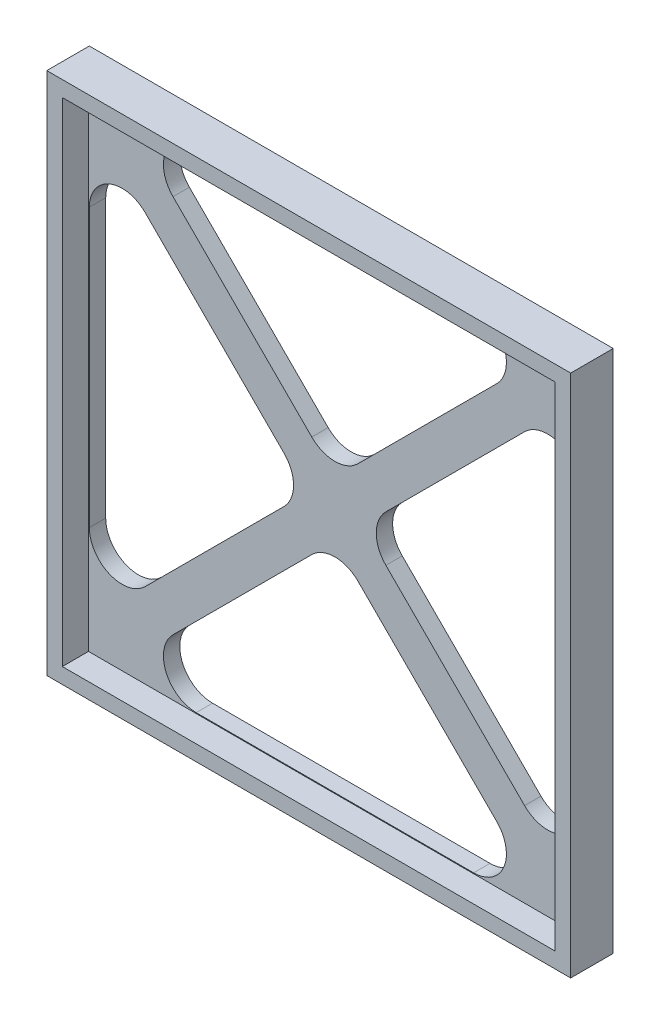
SolidWorks part; units mm, degrees
ref_plane "Front Plane" through (0, 0, 0) normal (0, 0, 1) x (1, 0, 0)
ref_plane "Top Plane" through (0, 0, 0) normal (0, 1, 0) x (1, 0, 0)
ref_plane "Right Plane" through (0, 0, 0) normal (1, 0, 0) x (0, 0, -1)
sketch "Sketch2" plane through (0, 0, 0) normal (0, 0, 1) x (1, 0, 0)
  line L0 (0, 80) -> (0, 0) construction
  line L1 (-80, 80) -> (80, 80)
  line L2 (-80, 80) -> (-80, -80)
  line L3 (-80, -80) -> (80, -80)
  line L4 (80, 80) -> (80, -80)
  line L5 (0, 0) -> (0, -80) construction
  dimension "D1" = 160
  dimension "D2" = 160
extrude "Boss-Extrude1" add sketch "Sketch2" along normal blind 5
sketch "Sketch3" plane through (0, 0, 5) normal (0, 0, 1) x (1, 0, 0)
  line L1 (75, -75) -> (-75, -75)
  line L2 (75, -75) -> (75, 75)
  line L3 (75, 75) -> (-75, 75)
  line L4 (-75, -75) -> (-75, 75)
  line L5 (75, -75) -> (-75, 75) construction
  line L6 (75, 75) -> (-75, -75) construction
  point P0 (0, 0)
  dimension "D1" = 150
  dimension "D2" = 150
extrude "Cut-Extrude1" cut sketch "Sketch3" against normal up to next
sketch "Sketch4" plane through (0, 0, 5) normal (0, 0, 1) x (1, 0, 0)
  line L0 (-75, 75) -> (75, -75) construction
  line L1 (75, 75) -> (-75, -75) construction
  line L2 (66.5147, 75) -> (0, 8.4853)
  line L3 (-75, 66.5147) -> (-8.4853, 0)
  line L4 (75, 66.5147) -> (8.4853, 0)
  line L5 (-66.5147, 75) -> (0, 8.4853)
  line L6 (-75, 75) -> (-75, 66.5147)
  line L7 (-75, 75) -> (-75, -75) construction
  line L8 (-75, 75) -> (-66.5147, 75)
  line L9 (75, 75) -> (-75, 75) construction
  line L10 (-75, -75) -> (-75, -66.5147)
  line L11 (-75, -75) -> (-66.5147, -75)
  line L12 (66.5147, -75) -> (75, -75)
  line L13 (-75, -75) -> (75, -75) construction
  line L14 (75, -75) -> (75, -66.5147)
  line L15 (75, -75) -> (75, 75) construction
  line L16 (75, 75) -> (75, 66.5147)
  line L17 (75, 75) -> (66.5147, 75)
  line L18 (70.7574, 79.2426) -> (-79.2426, -70.7574) construction
  line L19 (-70.7574, 79.2426) -> (79.2426, -70.7574) construction
  line L20 (-79.2426, 70.7574) -> (70.7574, -79.2426) construction
  line L21 (79.2426, 70.7574) -> (-70.7574, -79.2426) construction
  line L22 (0, -8.4853) -> (66.5147, -75)
  line L23 (8.4853, 0) -> (75, -66.5147)
  line L24 (-8.4853, 0) -> (-75, -66.5147)
  line L25 (0, -8.4853) -> (-66.5147, -75)
  dimension "D1" = 6
  dimension "D2" = 6
extrude "Boss-Extrude2" add sketch "Sketch4" against normal blind 5
sketch "Sketch5" plane through (0, 0, 5) normal (0, 0, 1) x (1, 0, 0)
  line L1 (-80, 80) -> (80, 80)
  line L2 (-80, 80) -> (-80, -80)
  line L3 (-80, -80) -> (80, -80)
  line L4 (80, 80) -> (80, -80)
  line L5 (75.25, -75.25) -> (-75.25, -75.25)
  line L6 (75.25, -75.25) -> (75.25, 75.25)
  line L7 (75.25, 75.25) -> (-75.25, 75.25)
  line L8 (-75.25, -75.25) -> (-75.25, 75.25)
  line L9 (75.25, -75.25) -> (-75.25, 75.25) construction
  line L10 (75.25, 75.25) -> (-75.25, -75.25) construction
  point P6 (0, 0)
  dimension "D1" = 150.5
  dimension "D2" = 150.5
extrude "Boss-Extrude3" add sketch "Sketch5" along normal blind 8
fillet "Fillet1" radius 10 12 edges at (75, 66.5147, 2.5) (75, -66.5147, 2.5) (8.4853, 0, 2.5) (66.5147, -75, 2.5) (-66.5147, -75, 2.5) (0, -8.4853, 2.5) (-75, -66.5147, 2.5) (-75, 66.5147, 2.5) (-8.4853, 0, 2.5) (-66.5147, 75, 2.5) (66.5147, 75, 2.5) (0, 8.4853, 2.5)
